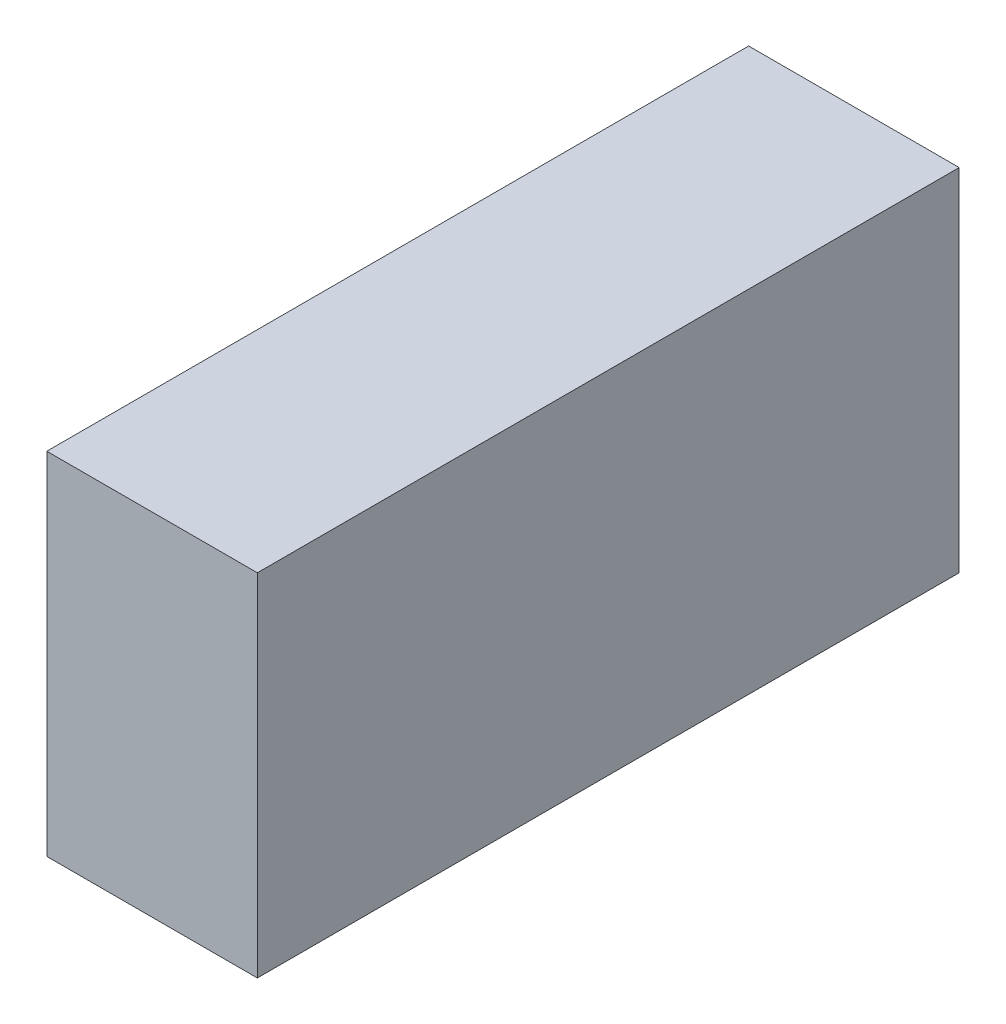
SolidWorks part; units mm, degrees
ref_plane "Alzado" through (0, 0, 0) normal (0, 0, 1) x (1, 0, 0)
ref_plane "Planta" through (0, 0, 0) normal (0, 1, 0) x (1, 0, 0)
ref_plane "Vista lateral" through (0, 0, 0) normal (1, 0, 0) x (0, 0, -1)
sketch "Croquis1" plane through (0, 0, 0) normal (0, 0, 1) x (1, 0, 0)
  line L1 (-60, -100) -> (60, -100)
  line L2 (-60, -100) -> (-60, 100)
  line L3 (-60, 100) -> (60, 100)
  line L4 (60, -100) -> (60, 100)
  line L5 (-60, -100) -> (60, 100) construction
  line L6 (-60, 100) -> (60, -100) construction
  point P0 (0, 0)
  dimension "D1" = 120
  dimension "D2" = 200
extrude "Saliente-Extruir1" add sketch "Croquis1" along normal blind 400
